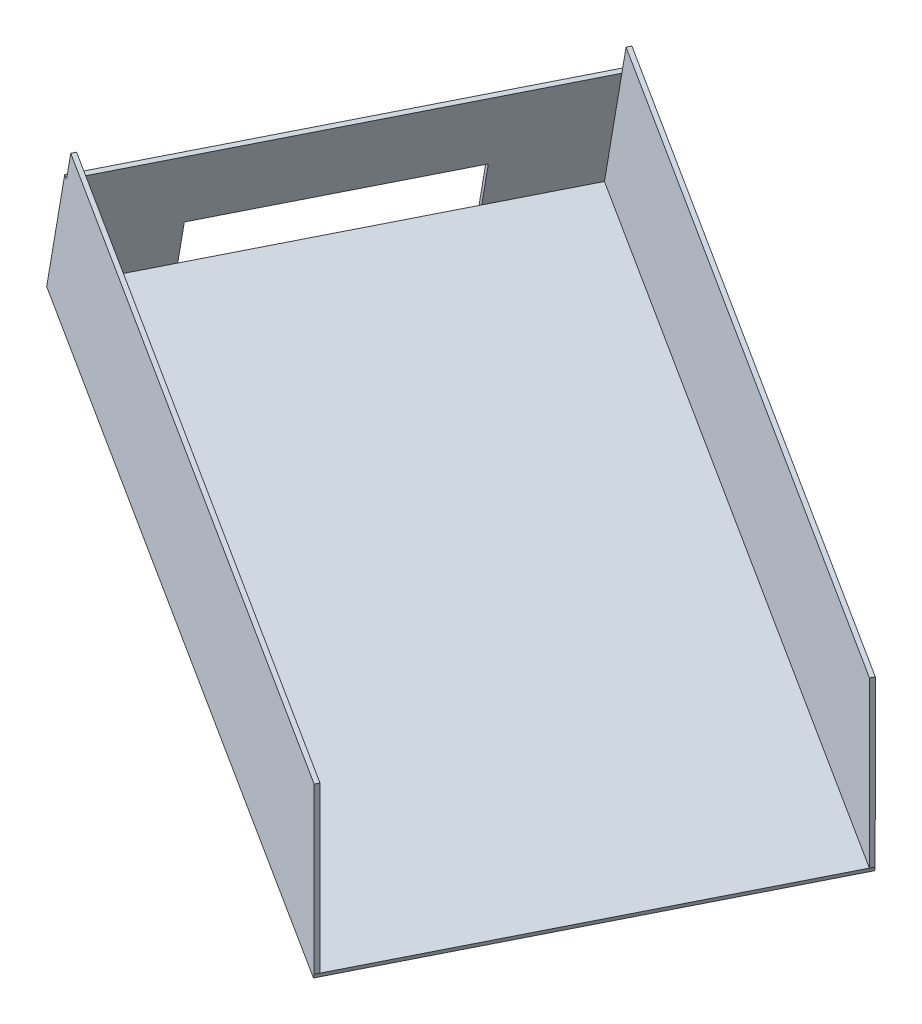
SolidWorks part; units mm, degrees
ref_plane "Front Plane" through (0, 0, 0) normal (0, 0, 1) x (1, 0, 0)
ref_plane "Top Plane" through (0, 0, 0) normal (0, 1, 0) x (1, 0, 0)
ref_plane "Right Plane" through (0, 0, 0) normal (1, 0, 0) x (0, 0, -1)
sketch "Sketch1" plane through (2274.7985, 0, -4526.6096) normal (-0.449, 0, 0.8935) x (0.8935, 0, 0.449)
  line L0 (-4499.4079, 647.1782) -> (-5368.6818, 930.8863) construction
  line L1 (-5368.6818, 930.8863) -> (-5370.652, 924.8496) construction
  line L2 (-5370.652, 924.8496) -> (-4501.3781, 641.1416) construction
  line L3 (-4501.3781, 641.1416) -> (-4499.4079, 647.1782) construction
  line L4 (-5370.652, 924.8496) -> (-5311.5462, 1105.9484) construction
  line L5 (-5311.5462, 1105.9484) -> (-5317.5828, 1107.9186) construction
  line L6 (-4499.092, 887.5422) -> (-4977.8137, 1043.7844)
  line L7 (-4981.8801, 1051.7912) -> (-4883.3704, 1353.6224)
  line L8 (-4883.3704, 1353.6224) -> (-5052.3959, 1408.7879)
  line L9 (-5244.5595, 1311.1936) -> (-5368.6818, 930.8863)
  line L10 (-5368.6818, 930.8863) -> (-4499.4079, 647.1782)
  line L11 (-4499.4079, 647.1782) -> (-4499.092, 887.5422)
  line L12 (-4499.092, 887.5422) -> (-4977.8137, 1043.7844)
  line L13 (-4981.8801, 1051.7912) -> (-4883.3704, 1353.6224)
  line L14 (-4883.3704, 1353.6224) -> (-5052.3959, 1408.7879)
  line L15 (-5244.5595, 1311.1936) -> (-5368.6818, 930.8863)
  line L16 (-5368.6818, 930.8863) -> (-4499.4079, 647.1782)
  line L17 (-4499.4079, 647.1782) -> (-4499.092, 887.5422)
  line L18 (-5317.5828, 1107.9186) -> (-5376.6886, 926.8198) construction
  line L19 (-5376.6886, 926.8198) -> (-5370.652, 924.8496) construction
  line L20 (-4499.4079, 647.1782) -> (-5368.6818, 930.8863)
  line L21 (-5368.6818, 930.8863) -> (-5370.652, 924.8496)
  line L22 (-5370.652, 924.8496) -> (-4501.3781, 641.1416)
  line L23 (-4501.3781, 641.1416) -> (-4499.4079, 647.1782)
  line L24 (-5370.652, 924.8496) -> (-5311.5462, 1105.9484)
  line L25 (-5311.5462, 1105.9484) -> (-5317.5828, 1107.9186)
  line L26 (-5317.5828, 1107.9186) -> (-5376.6886, 926.8198)
  line L27 (-5376.6886, 926.8198) -> (-5370.652, 924.8496)
  line L718 (-4977.8137, 1043.7844) -> (-5297.7548, 1148.2047)
  arc A2 (-4981.8801, 1051.7912) -> (-4977.8137, 1043.7844) centre (-4975.8435, 1049.821) ccw
  arc A3 (-5052.3959, 1408.7879) -> (-5244.5595, 1311.1936) centre (-5099.6806, 1263.9089) ccw
  arc A4 (-4981.8801, 1051.7912) -> (-4977.8137, 1043.7844) centre (-4975.8435, 1049.821) ccw
  arc A5 (-5052.3959, 1408.7879) -> (-5244.5595, 1311.1936) centre (-5099.6806, 1263.9089) ccw
  line M9 (-4499.092, 887.5422) -> (-4977.8137, 1043.7844)
  arc M10 (-4977.8137, 1043.7844) -> (-4981.8801, 1051.7912) centre (-4975.8435, 1049.821) cw
  line M11 (-4981.8801, 1051.7912) -> (-4883.3704, 1353.6224)
  line M12 (-4883.3704, 1353.6224) -> (-5052.3959, 1408.7879)
  arc M13 (-5052.3959, 1408.7879) -> (-5244.5595, 1311.1936) centre (-5099.6806, 1263.9089) ccw
  line M14 (-5244.5595, 1311.1936) -> (-5368.6818, 930.8863)
  line M15 (-5368.6818, 930.8863) -> (-4499.4079, 647.1782)
  line M16 (-4499.4079, 647.1782) -> (-4499.092, 887.5422)
  dimension "D1" = 0
extrude "Boss-Extrude1" add sketch "Sketch1" against normal up to surface (609.6 mm away) contours L15 M16 M9 M10 M11 M12 M13 M14 M15 | L26 L27 L21 L15 L25 | L22 L23 L21 M15
sketch "Sketch2" plane through (2277.6499, 0, -4532.2835) normal (0.449, 0, -0.8935) x (-0.8935, 0, -0.449)
  line L0 (4977.8137, 1043.7844) -> (5297.7548, 1148.2047)
  line L6 (4499.092, 887.5422) -> (4499.4079, 647.1782)
  line L7 (4499.4079, 647.1782) -> (5368.6818, 930.8863)
  line L8 (5368.6818, 930.8863) -> (5244.5595, 1311.1936)
  line L9 (5052.3959, 1408.7879) -> (4883.3704, 1353.6224)
  line L10 (4883.3704, 1353.6224) -> (4981.8801, 1051.7912)
  line L11 (4977.8137, 1043.7844) -> (4499.092, 887.5422)
  line L12 (4499.092, 887.5422) -> (4499.4079, 647.1782)
  line L13 (4499.4079, 647.1782) -> (5368.6818, 930.8863)
  line L14 (5368.6818, 930.8863) -> (5244.5595, 1311.1936)
  line L15 (5052.3959, 1408.7879) -> (4883.3704, 1353.6224)
  line L16 (4883.3704, 1353.6224) -> (4981.8801, 1051.7912)
  line L17 (4977.8137, 1043.7844) -> (4499.092, 887.5422)
  arc A2 (5244.5595, 1311.1936) -> (5052.3959, 1408.7879) centre (5099.6806, 1263.9089) ccw
  arc A3 (4977.8137, 1043.7844) -> (4981.8801, 1051.7912) centre (4975.8435, 1049.821) ccw
  arc A4 (5244.5595, 1311.1936) -> (5052.3959, 1408.7879) centre (5099.6806, 1263.9089) ccw
  arc A5 (4977.8137, 1043.7844) -> (4981.8801, 1051.7912) centre (4975.8435, 1049.821) ccw
  line M9 (4499.092, 887.5422) -> (4499.4079, 647.1782)
  line M10 (4499.4079, 647.1782) -> (5368.6818, 930.8863)
  line M11 (5368.6818, 930.8863) -> (5244.5595, 1311.1936)
  line M16 (4977.8137, 1043.7844) -> (4499.092, 887.5422)
  dimension "D1" = 0
extrude "Cut-Extrude1" cut sketch "Sketch2" along normal up to surface (596.9 mm away) contours L0 M16 M9 M10 M11
sketch "Sketch3" plane through (-4585.9525, 1675.1025, -2304.6207) normal (-0.8494, 0.3103, -0.4269) x (-0.401, 0.1465, 0.9043)
  line L4 (-5699.8117, 284.8852) -> (-5729.1601, 96.6595)
  line L5 (-5729.1601, 96.6595) -> (-5126.8378, 2.7446)
  line L6 (-5126.8378, 2.7446) -> (-5097.4894, 190.9703)
  line L7 (-5097.4894, 190.9703) -> (-5699.8117, 284.8852)
  line L8 (-5699.8117, 284.8852) -> (-5729.1601, 96.6595)
  line L9 (-5729.1601, 96.6595) -> (-5126.8378, 2.7446)
  line L10 (-5126.8378, 2.7446) -> (-5097.4894, 190.9703)
  line L11 (-5097.4894, 190.9703) -> (-5699.8117, 284.8852)
  line L16 (-5579.3885, 150.4276) -> (-5253.1306, 99.557)
  line L17 (-5253.1306, 99.557) -> (-5264.87, 24.2667)
  line L18 (-5264.87, 24.2667) -> (-5126.8378, 2.7446)
  line L19 (-5126.8378, 2.7446) -> (-5097.4894, 190.9703)
  line L20 (-5097.4894, 190.9703) -> (-5699.8117, 284.8852)
  line L21 (-5699.8117, 284.8852) -> (-5729.1601, 96.6595)
  line L22 (-5729.1601, 96.6595) -> (-5591.1279, 75.1373)
  line L23 (-5591.1279, 75.1373) -> (-5579.3885, 150.4276)
  line L24 (-5579.3885, 150.4276) -> (-5253.1306, 99.557)
  line L25 (-5253.1306, 99.557) -> (-5264.87, 24.2667)
  line L26 (-5264.87, 24.2667) -> (-5126.8378, 2.7446)
  line L27 (-5126.8378, 2.7446) -> (-5097.4894, 190.9703)
  line L28 (-5097.4894, 190.9703) -> (-5699.8117, 284.8852)
  line L29 (-5699.8117, 284.8852) -> (-5729.1601, 96.6595)
  line L30 (-5729.1601, 96.6595) -> (-5591.1279, 75.1373)
  line L31 (-5591.1279, 75.1373) -> (-5579.3885, 150.4276)
  dimension "D1" = 0
  dimension "D2" = 0
extrude "Cut-Extrude2" cut sketch "Sketch3" against normal up to surface (6.35 mm away) contours L31 L9 L25 L24
